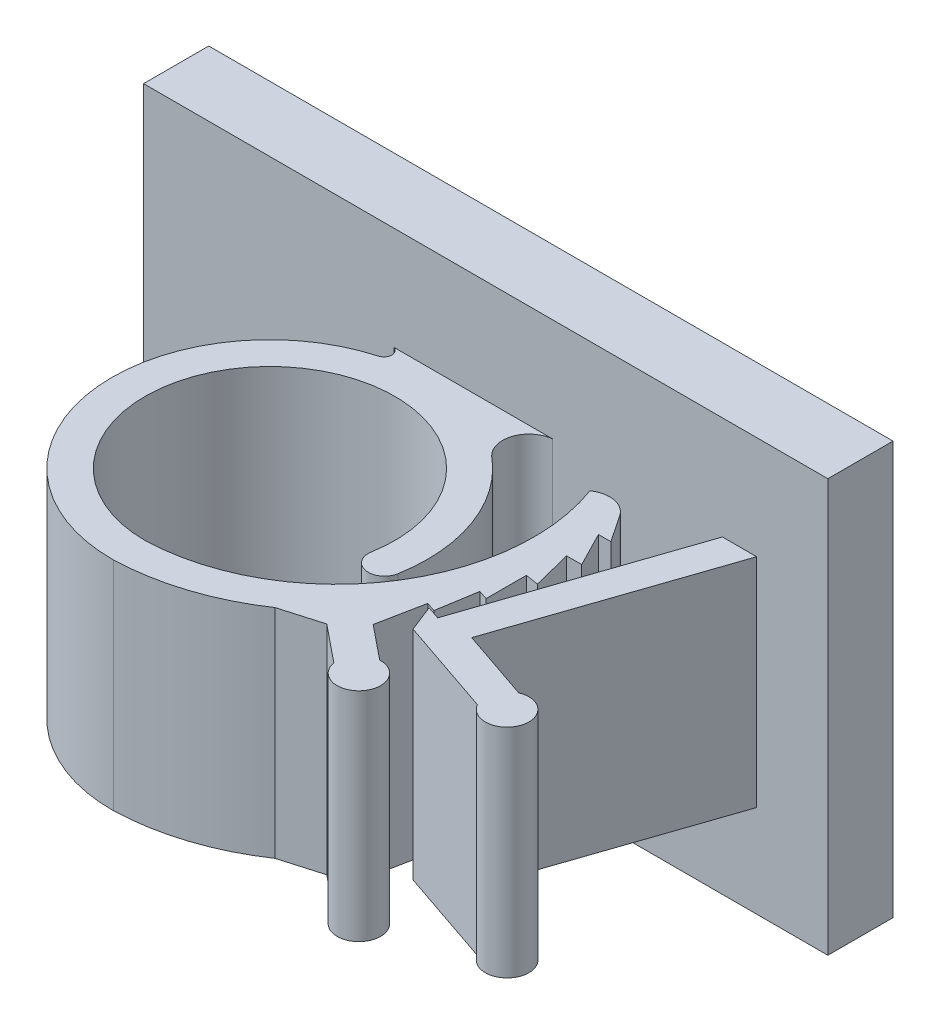
SolidWorks part; units mm, degrees
ref_plane "Face" through (0, 0, 0) normal (0, 0, 1) x (1, 0, 0)
ref_plane "Dessus" through (0, 0, 0) normal (0, 1, 0) x (1, 0, 0)
ref_plane "Droite" through (0, 0, 0) normal (1, 0, 0) x (0, 0, -1)
sketch "Esquisse1" plane through (0, 0, 0) normal (0, 0, 1) x (1, 0, 0)
  line L1 (-22.7432, 3.304) -> (8.7568, 3.304)
  line L2 (-22.7432, 3.304) -> (-22.7432, -15.696)
  line L3 (-22.7432, -15.696) -> (8.7568, -15.696)
  line L4 (8.7568, 3.304) -> (8.7568, -15.696)
  dimension "D1" = 31.5
  dimension "D2" = 19
extrude "Extrusion1" add sketch "Esquisse1" against normal blind 3
ref_plane "Plan1" through (0, -6.446, 0) normal (0, 1, 0) x (-1, 0, 0)
sketch "Esquisse2" plane through (0, -6.446, 0) normal (0, 1, 0) x (-1, 0, 0)
  line L0 (22.7432, -3) -> (22.7432, 0) construction
  line L1 (-8.7568, 0) -> (22.7432, 0) construction
  line L2 (-0.6839, 1.5037) -> (-1.5229, 2.7539)
  line L3 (3.9089, 0) -> (11.2253, 0)
  line L4 (-1.5229, 2.7539) -> (-0.9511, 2.7539)
  line L5 (-0.9511, 2.7539) -> (-1.7645, 4.3392)
  line L6 (-1.7645, 4.3392) -> (-1.0704, 4.3392)
  line L7 (-1.0704, 4.3392) -> (-1.5229, 6.1378)
  line L8 (-1.5229, 6.1378) -> (-0.9196, 6.0396)
  line L9 (-0.9196, 6.0396) -> (-0.9196, 7.8965)
  line L10 (-0.9196, 7.8965) -> (-0.4913, 7.7507)
  line L11 (-0.4913, 7.7507) -> (-0.1946, 9.5731)
  line L12 (-0.1946, 9.5731) -> (0.2316, 9.428)
  line L13 (0.2316, 9.428) -> (0.6469, 11.5262)
  line L14 (0.6469, 11.5262) -> (-0.9196, 12.7942)
  line L15 (0.0242, 9.5731) -> (-0.5736, 9.7767)
  line L16 (1.7351, 12.5752) -> (0.0242, 13.9601)
  line L17 (1.703, 9.1367) -> (2.2941, 12.1227) construction
  line L18 (1.7351, 12.5752) -> (3.5804, 13.1102)
  line L19 (2.2941, 12.1227) -> (0.0242, 13.9601) construction
  line L20 (0.0242, 9.5731) -> (-0.4535, 10.7922)
  line L21 (-0.4535, 10.7922) -> (-4.9466, 12.3224)
  line L22 (-5.4771, 0) -> (-2.1451, 9.7837)
  line L23 (-0.5736, 9.7767) -> (-3.9032, 0)
  line L24 (-5.4301, 10.9025) -> (-2.1451, 9.7837)
  line L29 (-3.9032, 0) -> (-5.4771, 0)
  arc A0 (3.5804, 8.6786) -> (9.2432, 13.431) centre (9.2432, 7.681) ccw
  arc A1 (9.1966, 14.9303) -> (11.2263, 0.7075) centre (9.2651, 7.6839) cw
  arc A2 (4.6287, 2.0891) -> (3.9089, 0) centre (3.7958, 1.2075) cw
  arc A3 (11.2263, 0.7075) -> (11.2253, 0) centre (11.3258, 0.3536) ccw
  arc A4 (2.1031, 8.9389) -> (3.5804, 8.6786) centre (2.8418, 8.8088) cw
  arc A7 (2.1031, 8.9389) -> (4.6287, 2.0891) centre (9.2432, 7.681) ccw
  arc A8 (9.2432, 13.431) -> (0.9857, 1.2075) centre (9.5258, 4.3392) ccw
  arc A9 (9.1966, 14.9303) -> (3.5804, 13.1102) centre (9.5258, 4.3392) ccw
  arc A10 (-0.6839, 1.5037) -> (0.9857, 1.2075) centre (0.299, 2.1905) ccw
  arc A11 (9.1966, 14.9303) -> (-0.4226, 0.6911) centre (9.5258, 4.3392) ccw construction
  arc A12 (-0.9196, 12.7942) -> (0.0242, 13.9601) centre (-0.9618, 13.7933) cw
  arc A13 (-4.9466, 12.3224) -> (-5.4301, 10.9025) centre (-5.8201, 11.8276) ccw
  dimension "D1" = 1.5
  dimension "D5" = 1
  dimension "D2" = 13.5
  dimension "D4" = 1
extrude "Extrusion2" add sketch "Esquisse2" along normal mid plane 10
